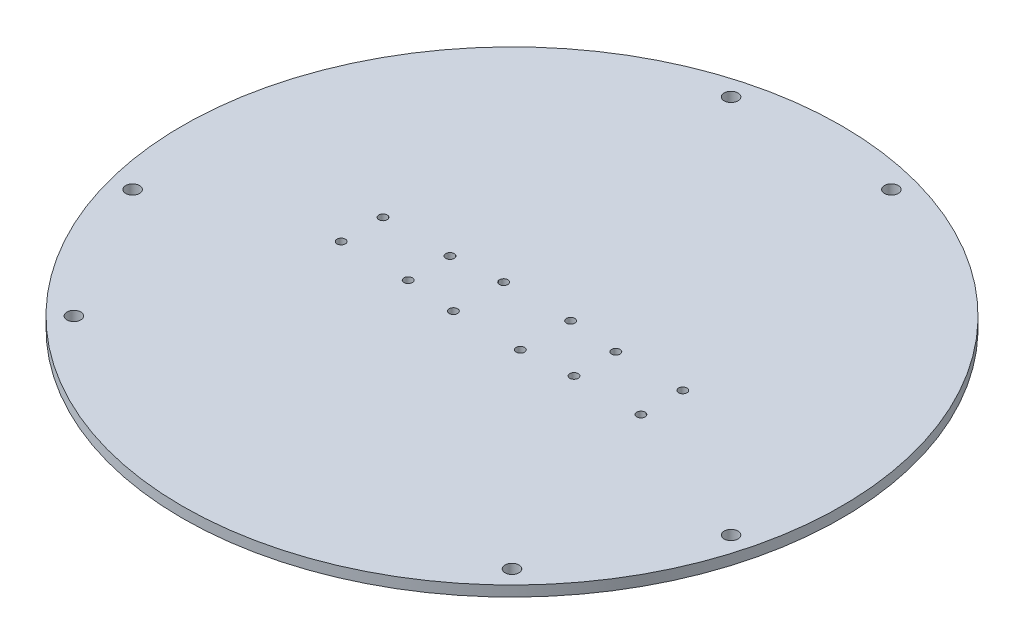
SolidWorks part; units mm, degrees
ref_plane "Front Plane" through (0, 0, 0) normal (0, 0, 1) x (1, 0, 0)
ref_plane "Top Plane" through (0, 0, 0) normal (0, 1, 0) x (1, 0, 0)
ref_plane "Right Plane" through (0, 0, 0) normal (1, 0, 0) x (0, 0, -1)
sketch "Sketch1" plane through (0, 0, 0) normal (0, 1, 0) x (1, 0, 0)
  line L0 (0, 100) -> (0, 0) construction
  line L1 (0, 0) -> (25.8819, 96.5926) construction
  line L2 (-100, 0) -> (100, 0) construction
  line L3 (-10.16, 7.62) -> (10.16, 7.62) construction
  line L4 (-10.16, 7.62) -> (-10.16, -7.62) construction
  line L5 (-10.16, -7.62) -> (10.16, -7.62) construction
  line L6 (10.16, 7.62) -> (10.16, -7.62) construction
  line L7 (-10.16, 7.62) -> (10.16, -7.62) construction
  line L8 (-10.16, -7.62) -> (10.16, 7.62) construction
  line L9 (-25.16, -6.35) -> (-45.48, 6.35) construction
  line L10 (25.16, 6.35) -> (45.48, 6.35) construction
  line L11 (25.16, 6.35) -> (25.16, -6.35) construction
  line L12 (25.16, -6.35) -> (45.48, -6.35) construction
  line L13 (45.48, 6.35) -> (45.48, -6.35) construction
  line L14 (25.16, 6.35) -> (45.48, -6.35) construction
  line L15 (25.16, -6.35) -> (45.48, 6.35) construction
  line L16 (-25.16, 6.35) -> (-45.48, -6.35) construction
  line L17 (-45.48, 6.35) -> (-45.48, -6.35) construction
  line L18 (-25.16, -6.35) -> (-45.48, -6.35) construction
  line L19 (-25.16, 6.35) -> (-25.16, -6.35) construction
  line L20 (-25.16, 6.35) -> (-45.48, 6.35) construction
  circle A0 centre (0, 0) radius 100
  circle A1 centre (24.329, 90.797) radius 2.1
  circle A2 centre (-24.329, 90.797) radius 2.1
  circle A3 centre (90.797, -24.329) radius 2.1
  circle A4 centre (66.468, -66.468) radius 2.1
  circle A5 centre (-66.468, -66.468) radius 2.1
  circle A6 centre (-90.797, -24.329) radius 2.1
  circle A12 centre (-10.16, 7.62) radius 1.27
  circle A13 centre (-10.16, -7.62) radius 1.27
  circle A14 centre (10.16, -7.62) radius 1.27
  circle A15 centre (10.16, 7.62) radius 1.27
  circle A16 centre (25.16, 6.35) radius 1.27
  circle A17 centre (25.16, -6.35) radius 1.27
  circle A18 centre (45.48, -6.35) radius 1.27
  circle A19 centre (45.48, 6.35) radius 1.27
  circle A20 centre (-45.48, 6.35) radius 1.27
  circle A21 centre (-45.48, -6.35) radius 1.27
  circle A22 centre (-25.16, -6.35) radius 1.27
  circle A23 centre (-25.16, 6.35) radius 1.27
  point P27 (35.32, 0)
  point P44 (-35.32, 0)
  point P45 (0, 0)
  dimension "D1" = 200
  dimension "D3" = 4.2
  dimension "D6" = 2.54
  dimension "D2" = 20.32
  dimension "D4" = 6
  dimension "D5" = 15.24
  dimension "D7" = 12.7
  dimension "D8" = 20.32
  dimension "D9" = 15
  dimension "D10" = 15
  dimension "D11" = 90
extrude "Boss-Extrude1" add sketch "Sketch1" along normal blind 3.175
